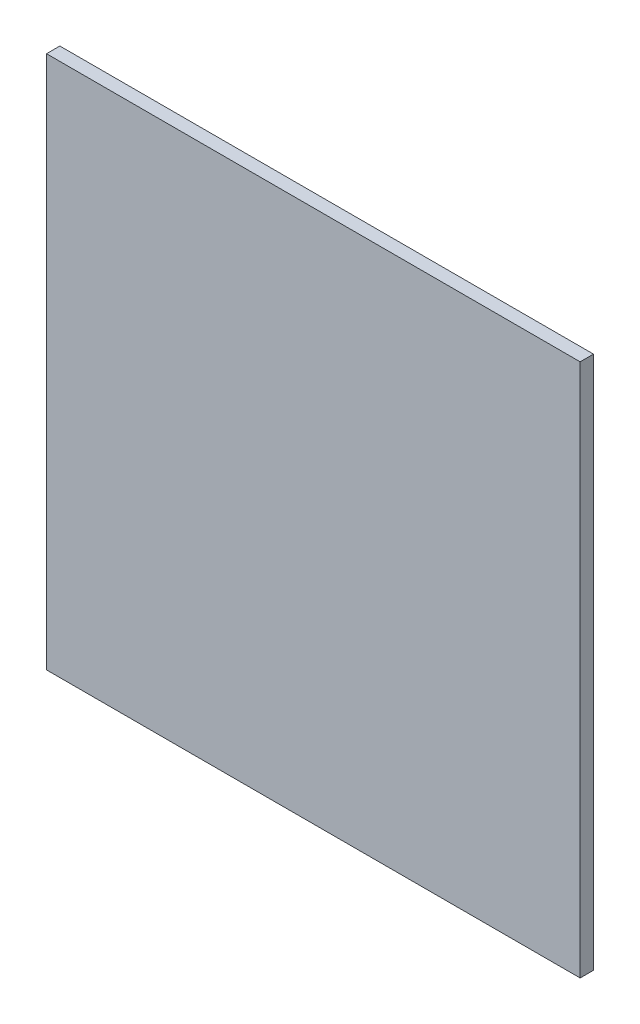
SolidWorks part; units mm, degrees
ref_plane "Front Plane" through (0, 0, 0) normal (0, 0, 1) x (1, 0, 0)
ref_plane "Top Plane" through (0, 0, 0) normal (0, 1, 0) x (1, 0, 0)
ref_plane "Right Plane" through (0, 0, 0) normal (1, 0, 0) x (0, 0, -1)
sketch "Sketch1" plane through (0, 0, 0) normal (0, 0, 1) x (1, 0, 0)
  line L1 (0, 0) -> (100, 0)
  line L2 (0, 0) -> (0, 100)
  line L3 (0, 100) -> (100, 100)
  line L4 (100, 0) -> (100, 100)
  dimension "D1" = 100
  dimension "D2" = 100
extrude "Boss-Extrude1" add sketch "Sketch1" along normal blind 2.5 contours L3 L4 L1 L2
sketch "Sketch2" plane through (0, 0, 2.5) normal (0, 0, 1) x (1, 0, 0)
  line L5 (0, 50) -> (12.5, 50) construction
  line L6 (0, 0) -> (0, 100) construction
  circle A1 centre (13.75, 50) radius 1.25
  dimension "D3" = 2.5
  dimension "D4" = 12.5
sketch "Sketch4" plane through (0, 0, 2.5) normal (0, 0, 1) x (1, 0, 0)
  line L0 (100, 50) -> (87.4995, 50) construction
  line L1 (100, 0) -> (100, 100) construction
  line L2 (86.25, 49.9644) -> (43, 49.9644) construction
  circle A0 centre (86.25, 49.9644) radius 1.25
  circle A1 centre (43, 49.9644) radius 1.25
  point P7 (100, 50)
  dimension "D2" = 2.5
  dimension "D3" = 43.25
  dimension "D1" = 13.75
